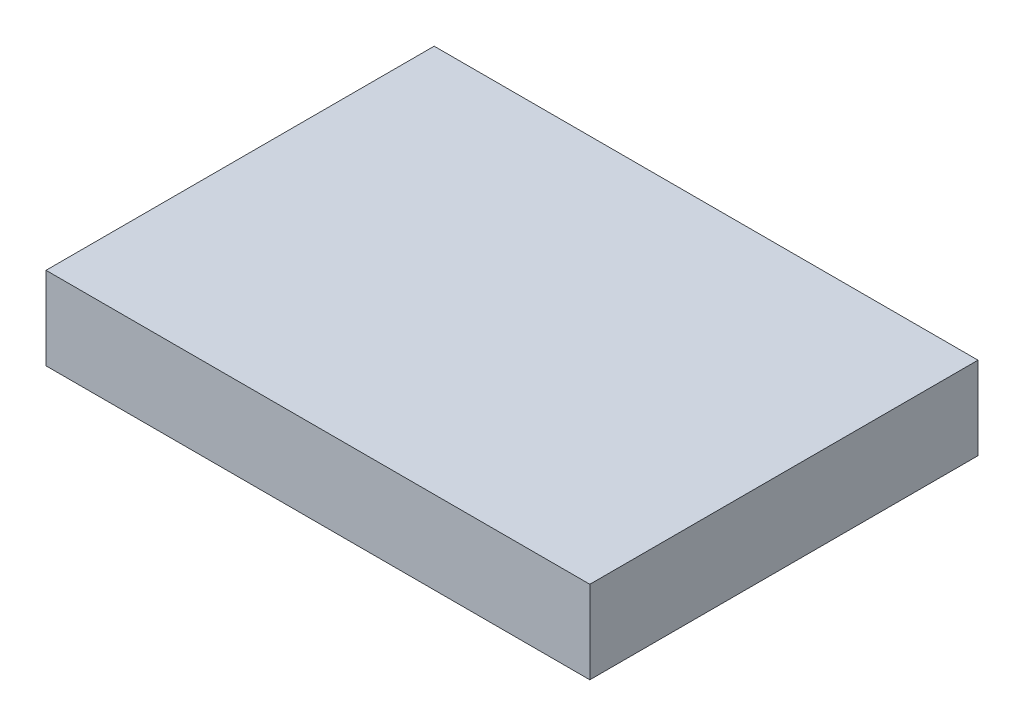
SolidWorks part; units mm, degrees
ref_plane "Front Plane" through (0, 0, 0) normal (0, 0, 1) x (1, 0, 0)
ref_plane "Top Plane" through (0, 0, 0) normal (0, 1, 0) x (1, 0, 0)
ref_plane "Right Plane" through (0, 0, 0) normal (1, 0, 0) x (0, 0, -1)
sketch "Sketch1" plane through (0, 0, 0) normal (0, 1, 0) x (1, 0, 0)
  line L1 (-35.052, -25.019) -> (35.052, -25.019)
  line L2 (-35.052, -25.019) -> (-35.052, 25.019)
  line L3 (-35.052, 25.019) -> (35.052, 25.019)
  line L4 (35.052, -25.019) -> (35.052, 25.019)
  line L5 (-35.052, -25.019) -> (35.052, 25.019) construction
  line L6 (-35.052, 25.019) -> (35.052, -25.019) construction
  point P0 (0, 0)
  dimension "D1" = 50.038
  dimension "D2" = 70.104
extrude "Boss-Extrude1" add sketch "Sketch1" along normal blind 10.668
